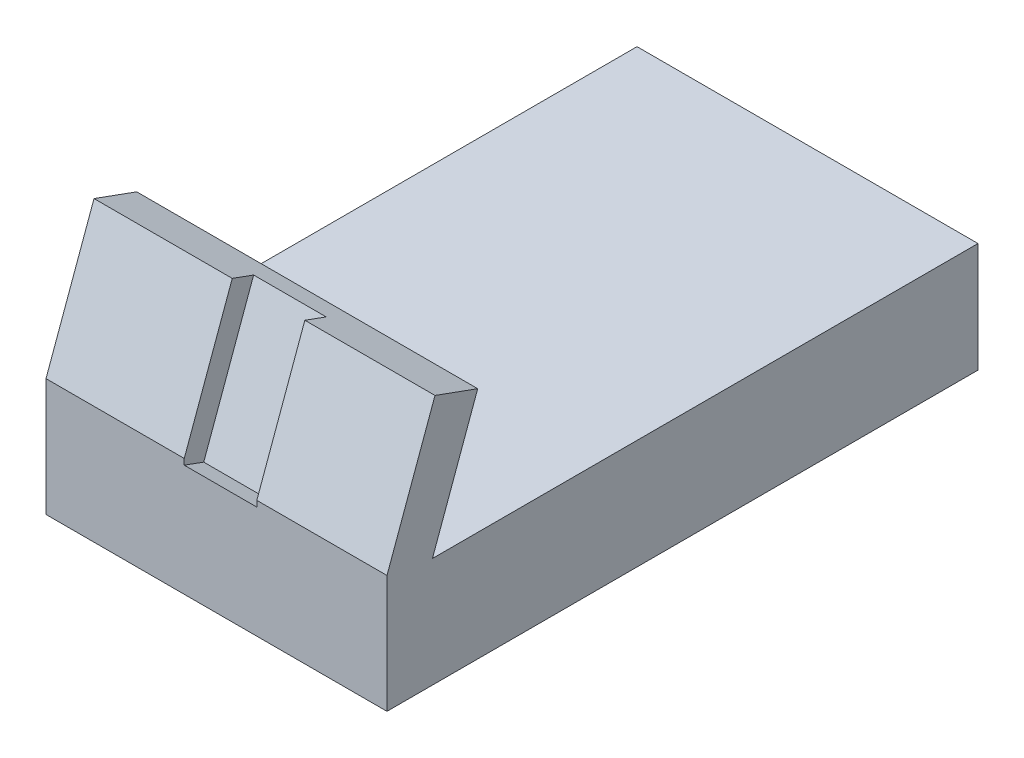
SolidWorks part; units mm, degrees
ref_plane "Front Plane" through (0, 0, 0) normal (0, 0, 1) x (1, 0, 0)
ref_plane "Top Plane" through (0, 0, 0) normal (0, 1, 0) x (1, 0, 0)
ref_plane "Right Plane" through (0, 0, 0) normal (1, 0, 0) x (0, 0, -1)
sketch "Sketch1" plane through (0, 0, 0) normal (1, 0, 0) x (0, 0, -1)
  line L1 (65, -12.06) -> (-65, -12.06)
  line L2 (65, -12.06) -> (65, 12.06)
  line L3 (65, 12.06) -> (-55, 12.06)
  line L6 (-65, 13.8233) -> (-54.4384, 42.841)
  line L7 (-55, 12.06) -> (-45.0404, 39.4238)
  line L8 (-54.4384, 42.841) -> (-45.0404, 39.4238)
  line L9 (-65, 13.8233) -> (-65, -12.06)
  point P0 (0, 0)
  dimension "D1" = 130
  dimension "D2" = 24.12
  dimension "D4" = 70
extrude "Boss-Extrude1" add sketch "Sketch1" against normal blind 75
sketch "Sketch2" plane through (0, 22.5076, 61.8392) normal (0, 0.342, 0.9397) x (1, 0, 0)
  line L3 (-28.6318, -10.4517) -> (-44.5918, -10.4517)
  line L5 (-28.6318, 29.5483) -> (-44.5918, 29.5483)
  line L6 (-44.5918, -10.4517) -> (-44.5918, 29.5483)
  line L7 (-28.6318, -10.4517) -> (-28.6318, 29.5483)
  dimension "D1" = 40
  dimension "D2" = 15.96
extrude "Cut-Extrude1" cut sketch "Sketch2" against normal blind 5
